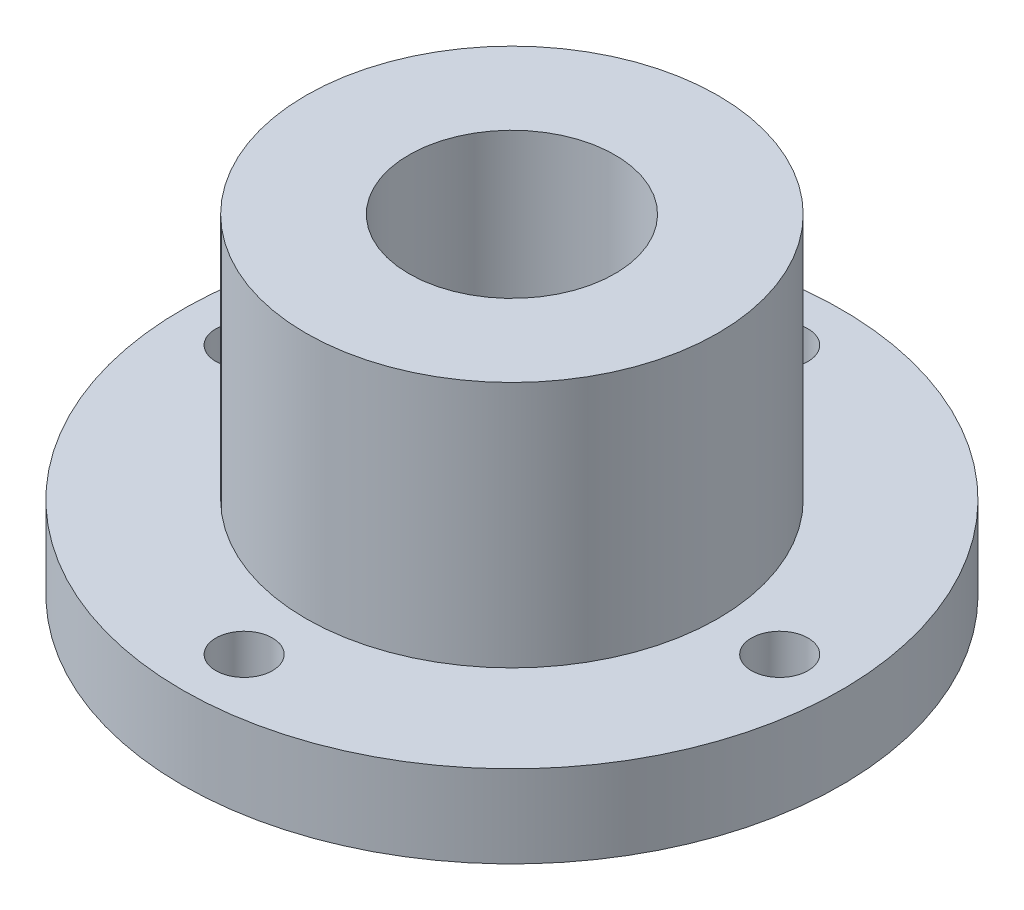
SolidWorks part; units mm, degrees
ref_plane "前视基准面" through (0, 0, 0) normal (0, 0, 1) x (1, 0, 0)
ref_plane "上视基准面" through (0, 0, 0) normal (0, 1, 0) x (1, 0, 0)
ref_plane "右视基准面" through (0, 0, 0) normal (1, 0, 0) x (0, 0, -1)
sketch "草图1" plane through (0, 0, 0) normal (0, 0, 1) x (1, 0, 0)
  line L0 (-10, 0) -> (-32, 0)
  line L1 (-32, 0) -> (-32, 8)
  line L2 (-32, 8) -> (-20, 8)
  line L3 (-20, 8) -> (-20, 32)
  line L4 (-20, 32) -> (-10, 32)
  line L5 (-10, 32) -> (-10, 0)
  line L6 (0, 79.3527) -> (0, -17.2991) construction
  dimension "D1" = 20
  dimension "D2" = 32
  dimension "D3" = 40
  dimension "D4" = 64
  dimension "D5" = 8
revolve "旋转1" add sketch "草图1" angle 360 about L6
sketch "草图2" plane through (0, 8, 0) normal (0, 1, 0) x (1, 0, 0)
  circle A0 centre (0, 26) radius 2.75
  circle A1 centre (26, 0) radius 2.75
  circle A2 centre (0, -26) radius 2.75
  circle A3 centre (-26, 0) radius 2.75
  point P12 (0, 0)
  dimension "D1" = 26
  dimension "D2" = 5.5
  dimension "D3" = 4
extrude "切除-拉伸1" cut sketch "草图2" against normal blind 10
